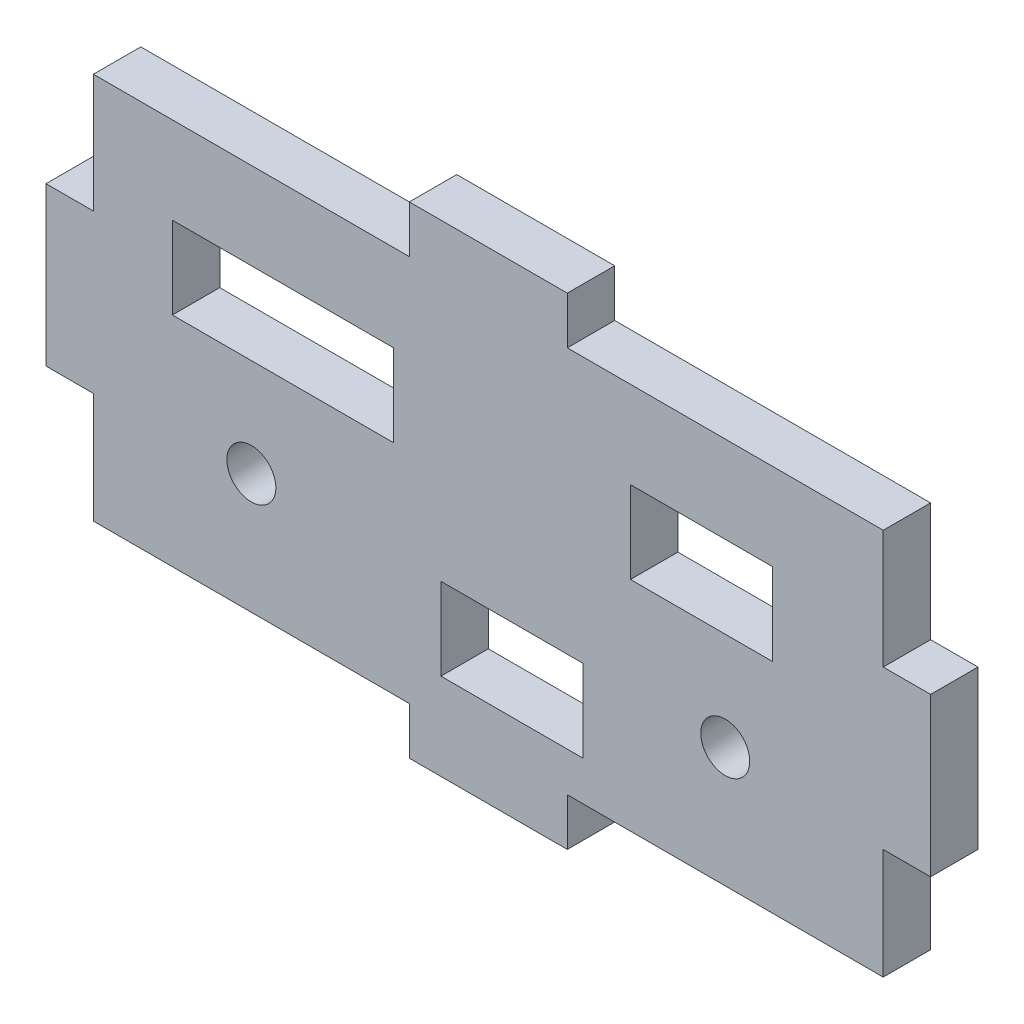
SolidWorks part; units mm, degrees
ref_plane "Front Plane" through (0, 0, 0) normal (0, 0, 1) x (1, 0, 0)
ref_plane "Top Plane" through (0, 0, 0) normal (0, 1, 0) x (1, 0, 0)
ref_plane "Right Plane" through (0, 0, 0) normal (1, 0, 0) x (0, 0, -1)
sketch "Sketch1" plane through (0, 0, 0) normal (0, 0, 1) x (-1, 0, 0)
  line L0 (-3.4763, -7.8376) -> (-3.4763, -4.8376)
  line L1 (-3.4763, -4.8376) -> (6.5237, -4.8376)
  line L2 (6.5237, -7.8376) -> (26.5237, -7.8376)
  line L3 (26.5237, -7.8376) -> (26.5237, -14.8376)
  line L4 (26.5237, -14.8376) -> (29.5237, -14.8376)
  line L5 (29.5237, -14.8376) -> (29.5237, -24.8376)
  line L6 (29.5237, -24.8376) -> (26.5237, -24.8376)
  line L7 (26.5237, -24.8376) -> (26.5237, -32.3376)
  line L8 (29.0237, -2.3376) -> (46.0636, -19.8376) construction
  line L9 (6.5237, -4.8376) -> (6.5237, -7.8376)
  line L10 (-3.4763, -7.8376) -> (-23.4763, -7.8376)
  line L11 (46.0636, -19.8376) -> (29.0237, -37.3376) construction
  line L12 (1.5237, -4.8376) -> (1.5237, -64.0619) construction
  line L13 (-23.4763, -24.8376) -> (-23.4763, -32.3376)
  line L14 (-26.4763, -24.8376) -> (-23.4763, -24.8376)
  line L15 (-26.4763, -14.8376) -> (-26.4763, -24.8376)
  line L16 (-23.4763, -14.8376) -> (-26.4763, -14.8376)
  line L17 (-23.4763, -7.8376) -> (-23.4763, -14.8376)
  line L18 (-26.4763, -19.8376) -> (-16.6963, -19.8376) construction
  line L19 (26.5237, -32.3376) -> (26.5237, -39.8376) construction
  line L20 (12.5029, -7.8376) -> (12.5029, -32.3376) construction
  line L21 (12.5029, -20.0876) -> (75.1393, -20.0876) construction
  line L22 (-3.4763, -32.3376) -> (-23.4763, -32.3376)
  line L23 (6.5237, -35.3376) -> (6.5237, -32.3376)
  line L24 (6.5237, -32.3376) -> (26.5237, -32.3376)
  line L25 (-3.4763, -35.3376) -> (6.5237, -35.3376)
  line L26 (-3.4763, -32.3376) -> (-3.4763, -35.3376)
  dimension "D1" = 20
  dimension "D2" = 3
  dimension "D3" = 10
  dimension "D4" = 10
  dimension "D5" = 3
  dimension "D6" = 50
  dimension "D7" = 7
  dimension "D8" = 7.5
extrude "Boss-Extrude1" add sketch "Sketch1" along normal blind 3
sketch "Sketch4" plane through (0, 0, 3) normal (0, 0, 1) x (1, 0, 0)
  line L1 (13.4763, 7.8376) -> (13.4763, 15.4376) construction
  line L4 (-1.5237, 35.3376) -> (-1.5237, 4.8376) construction
  line L6 (-29.0237, 15.4376) -> (25.9763, 15.4376) construction
  line L8 (26.4763, 19.8376) -> (-29.5237, 19.8376) construction
  line L12 (3.4763, 7.8376) -> (23.4763, 7.8376) construction
  line L13 (23.4763, 32.3376) -> (3.4763, 32.3376) construction
  line L20 (25.9763, 15.4376) -> (25.9763, 35.3876) construction
  line L22 (-4.5237, 10.3376) -> (4.4763, 15.5376) construction
  line L29 (-4.5237, 15.5376) -> (4.4763, 10.3376) construction
  line L30 (7.4763, 21.6376) -> (16.4763, 26.8376) construction
  line L32 (7.4763, 26.8376) -> (16.4763, 21.6376) construction
  line L33 (-21.5237, 21.6376) -> (-7.5237, 26.8376) construction
  line L34 (-21.5237, 26.8376) -> (-7.5237, 21.6376) construction
  line L35 (-29.0237, 24.2376) -> (-29.0237, 4.2876) construction
  line L36 (4.4763, 15.5376) -> (4.4763, 10.3376)
  line L37 (-4.5237, 10.3376) -> (4.4763, 10.3376)
  line L38 (-4.5237, 15.5376) -> (-4.5237, 10.3376)
  line L39 (-4.5237, 15.5376) -> (4.4763, 15.5376)
  line L40 (16.4763, 26.8376) -> (16.4763, 21.6376)
  line L41 (7.4763, 21.6376) -> (16.4763, 21.6376)
  line L42 (7.4763, 26.8376) -> (7.4763, 21.6376)
  line L43 (7.4763, 26.8376) -> (16.4763, 26.8376)
  line L44 (-7.5237, 26.8376) -> (-7.5237, 21.6376)
  line L45 (-21.5237, 21.6376) -> (-7.5237, 21.6376)
  line L46 (-21.5237, 26.8376) -> (-21.5237, 21.6376)
  line L47 (-21.5237, 26.8376) -> (-7.5237, 26.8376)
  circle A0 centre (-1.5237, 19.8376) radius 1.7837 construction
  circle A1 centre (13.4763, 15.4376) radius 1.55
  circle A2 centre (-16.5237, 15.4376) radius 1.55
  point P5 (11.9763, 26.8376)
  point P68 (11.9763, 24.2376)
  point P69 (-14.5237, 24.2376)
  dimension "D1" = 9
  dimension "D9" = 3.1
  dimension "D2" = 5.2
  dimension "D3" = 14
  dimension "D4" = 9
  dimension "D5" = 15
  dimension "D6" = 5.5
  dimension "D7" = 6.1
  dimension "D8" = 3
extrude "Cut-Extrude1" cut sketch "Sketch4" against normal up to vertex (3 mm away)
